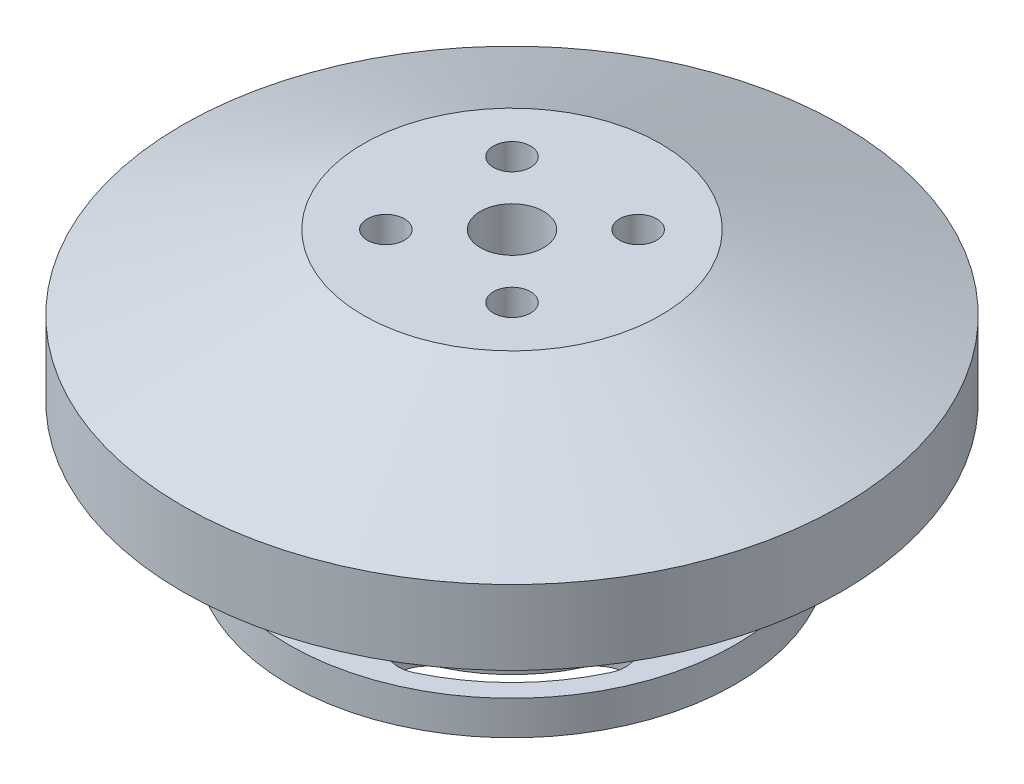
SolidWorks part; units mm, degrees
ref_plane "Plan de face" through (0, 0, 0) normal (0, 0, 1) x (1, 0, 0)
ref_plane "Plan de dessus" through (0, 0, 0) normal (0, 1, 0) x (1, 0, 0)
ref_plane "Plan de droite" through (0, 0, 0) normal (1, 0, 0) x (0, 0, -1)
sketch "Esquisse1" plane through (0, 0, 0) normal (0, 1, 0) x (1, 0, 0)
  circle A0 centre (0, 0) radius 22.175
  dimension "D1" = 44.35
extrude "Boss.-Extru.1" add sketch "Esquisse1" along normal blind 5
sketch "Esquisse2" plane through (0, 0, 0) normal (0, 0, 1) x (1, 0, 0)
  line L0 (0, 17.6967) -> (0, -9.3383) construction
  line L1 (0, 10) -> (-10, 10)
  line L2 (-10, 10) -> (-22.175, 5)
  line L3 (-22.175, 5) -> (0, 5)
  line L4 (22.175, 5) -> (-22.175, 5) construction
  line L5 (0, 5) -> (0, 10)
  dimension "D1" = 20
  dimension "D2" = 5
revolve "Révolution1" add sketch "Esquisse2" angle 360 about L0
chamfer "Chanfrein1" [suppressed] distance 0.5 angle 45
sketch "Esquisse5" [suppressed] plane through (0, 0, 0) normal (0, 0, 1) x (1, 0, 0)
  line L0 (0, 15.7888) -> (0, -12.4636) construction
  line L6 (0, 9) -> (0, 1)
  line L11 (9.8027, 9) -> (-10, 9)
  line L12 (-22.175, 1) -> (21.175, 1)
  line L13 (20.7612, 4.4996) -> (9.8027, 9)
  line L14 (21.175, 4.0858) -> (20.7612, 4.4996)
  line L15 (21.175, 1) -> (21.175, 4.0858)
  line L16 (9.8027, 9) -> (0, 9)
  line L17 (0, 1) -> (21.175, 1)
  line L18 (20.7612, 4.4996) -> (9.8027, 9)
  line L19 (21.175, 4.0858) -> (20.7612, 4.4996)
  line L20 (21.175, 1) -> (21.175, 4.0858)
  dimension "D1" = 1
revolve "Enlèvement de matière-Révolution1" [suppressed] cut sketch "Esquisse5" angle 360 about L6
sketch "Esquisse6" plane through (0, 10, 0) normal (0, 1, 0) x (1, 0, 0)
  line L0 (0, 6) -> (0, 0) construction
  line L1 (0, 0) -> (4.2426, 4.2426) construction
  circle A0 centre (0, 0) radius 6 construction
  point P3 (4.2426, 4.2426)
  point P9 (4.2426, -4.2426)
  point P10 (-4.2426, -4.2426)
  point P11 (-4.2426, 4.2426)
  point P12 (0, 0)
  dimension "D1" = 12
  dimension "D2" = 45
  dimension "D3" = 4
hole_wizard "Trou taraudé M31" positions "Esquisse3D1" profile "Esquisse7" tap size "M3" standard "ISO"
sketch3d "Esquisse3D1"
  point P0 (4.2426, 10, -4.2426)
  point P3 (4.2426, 10, 4.2426)
  point P6 (-4.2426, 10, 4.2426)
  point P9 (-4.2426, 10, -4.2426)
sketch "Esquisse7" plane through (4.2426, 10, -4.2426) normal (1, 0, 0) x (0, 0, 1)
  line L0 (0, 0) -> (0, 6.2511)
  line L1 (0, 6.2511) -> (1.25, 5.5)
  line L2 (1.25, 5.5) -> (1.25, 0)
  line L5 (1.25, 0) -> (0, 0)
  line L10 (0, 6.2511) -> (-1.25, 5.5) construction
  line L11 (0, -6.35) -> (0, 107.95) construction
  dimension "Diamètre du trou pour taraudage" = 2.5
  dimension "Profondeur du trou pour taraudage" = 5.5
  dimension "Angle de pointe" = 118
cosmetic thread "Filetage de perçage1" parameters "D1"=1, "D2"=3
cosmetic thread "Filetage de perçage2" parameters "D1"=1, "D2"=3
cosmetic thread "Filetage de perçage3" parameters "D1"=1, "D2"=3
cosmetic thread "Filetage de perçage4" parameters "D1"=1, "D2"=3
sketch "Esquisse8" [suppressed] plane through (0, 10, 0) normal (0, 1, 0) x (1, 0, 0)
  line L0 (0, 24.7209) -> (0, 0) construction
  line L1 (0, 0) -> (14.6239, 23.3628) construction
  line L2 (0, 0) -> (2.8128, 22.7623) construction
  line L3 (0, 0) -> (19.245, 12.4767) construction
  circle A3 centre (0, 0) radius 22.175 construction
  arc A4 (18.1694, 12.7124) -> (3.4948, 21.8979) centre (0, 0) ccw
  arc A5 (20.0939, -9.3789) -> (20.7115, 7.9224) centre (0, 0) ccw
  arc A6 (1.9246, -22.0913) -> (17.2167, -13.9755) centre (0, 0) ccw
  arc A7 (-18.1694, -12.7124) -> (-3.4948, -21.8979) centre (0, 0) ccw
  arc A8 (-20.0939, 9.3789) -> (-20.7115, -7.9224) centre (0, 0) ccw
  arc A9 (-1.9246, 22.0913) -> (-17.2167, 13.9755) centre (0, 0) ccw
  ellipse E0 centre (14.6239, 23.3628) end of major axis (4.5893, 7.3318) minor radius 9.3493 (3.4948, 21.8979) -> (18.1694, 12.7124) ccw
  ellipse E1 centre (28.7047, -1.0246) end of major axis (8.888, -0.3173) minor radius 9.5331 (20.7115, 7.9224) -> (20.0939, -9.3789) ccw
  ellipse E2 centre (13.465, -25.3713) end of major axis (4.1692, -7.8558) minor radius 9.5331 (17.2167, -13.9755) -> (1.9246, -22.0913) ccw
  ellipse E3 centre (-15.2397, -24.3467) end of major axis (-4.7187, -7.5386) minor radius 9.5331 (-3.4948, -21.8979) -> (-18.1694, -12.7124) ccw
  ellipse E4 centre (-28.7047, 1.0246) end of major axis (-8.888, 0.3173) minor radius 9.5331 (-20.7115, -7.9224) -> (-20.0939, 9.3789) ccw
  ellipse E5 centre (-13.465, 25.3713) end of major axis (-4.1692, 7.8558) minor radius 9.5331 (-17.2167, 13.9755) -> (-1.9246, 22.0913) ccw
  point P51 (0, 0)
  dimension "D1" = 32.044
  dimension "D2" = 25
  dimension "D3" = 6
extrude "Enlèv. mat.-Extru.1" [suppressed] cut sketch "Esquisse8" against normal blind 5.5
chamfer "Chanfrein2" [suppressed] distance 0.5 angle 45
chamfer "Chanfrein3" [suppressed] distance 0.5 angle 45
chamfer "Chanfrein4" [suppressed] distance 0.25 angle 45
sketch "Esquisse9" plane through (0, 0, 0) normal (0, -1, 0) x (1, 0, 0)
  circle A0 centre (0, 0) radius 8
  dimension "D1" = 16
extrude "Boss.-Extru.2" add sketch "Esquisse9" along normal blind 6.7 and the other way blind 5.5 separate body
sketch "Esquisse10" plane through (0, -6.7, 0) normal (0, -1, 0) x (1, 0, 0)
  circle A0 centre (0, 0) radius 15
  dimension "D1" = 30
extrude "Boss.-Extru.3" add sketch "Esquisse10" along normal blind 2.3
sketch "Esquisse11" plane through (0, -9, 0) normal (0, -1, 0) x (1, 0, 0)
  point P0 (0, 12.5)
  point P5 (12.5, 0)
  point P6 (0, -12.5)
  point P7 (-12.5, 0)
  point P8 (0, 0)
  dimension "D1" = 12.5
  dimension "D2" = 4
hole_wizard "Trou taraudé M32" positions "Esquisse3D2" profile "Esquisse12" tap size "M3" standard "ISO"
sketch3d "Esquisse3D2"
  point P0 (0, -9, 12.5)
  point P3 (12.5, -9, 0)
  point P6 (-12.5, -9, 0)
  point P9 (0, -9, -12.5)
sketch "Esquisse12" plane through (0, -9, 12.5) normal (1, 0, 0) x (0, 0, -1)
  line L0 (0, 0) -> (0, 6.2511)
  line L1 (0, 6.2511) -> (1.25, 5.5)
  line L2 (1.25, 5.5) -> (1.25, 0)
  line L5 (1.25, 0) -> (0, 0)
  line L10 (0, 6.2511) -> (-1.25, 5.5) construction
  line L11 (0, -6.35) -> (0, 107.95) construction
  dimension "Diamètre du trou pour taraudage" = 2.5
  dimension "Profondeur du trou pour taraudage" = 5.5
  dimension "Angle de pointe" = 118
cosmetic thread "Filetage de perçage5" parameters "D1"=2.3, "D2"=3
cosmetic thread "Filetage de perçage6" parameters "D1"=2.3, "D2"=3
cosmetic thread "Filetage de perçage7" parameters "D1"=2.3, "D2"=3
cosmetic thread "Filetage de perçage8" parameters "D1"=2.3, "D2"=3
sketch "Esquisse13" plane through (0, -9, 0) normal (0, -1, 0) x (1, 0, 0)
  line L0 (-8.3085, 8.3085) -> (0, 0) construction
  line L1 (0, 0) -> (0, 12.5) construction
  line L2 (-4.9658, 10.6491) -> (0, 0) construction
  line L3 (0, 0) -> (-10.6491, 4.9658) construction
  circle A0 centre (0, 0) radius 11.75 construction
  arc A1 (-10.6491, 4.9658) -> (-4.9658, 10.6491) centre (0, 0) cw construction
  arc A2 (-5.7899, 12.4164) -> (-12.4164, 5.7899) centre (0, 0) ccw
  arc A3 (-4.1417, 8.8818) -> (-8.8818, 4.1417) centre (0, 0) ccw
  arc A4 (-4.1417, 8.8818) -> (-5.7899, 12.4164) centre (-4.9658, 10.6491) ccw
  arc A5 (-12.4164, 5.7899) -> (-8.8818, 4.1417) centre (-10.6491, 4.9658) ccw
  arc A6 (4.9658, 10.6491) -> (10.6491, 4.9658) centre (0, 0) cw construction
  arc A7 (12.4164, 5.7899) -> (5.7899, 12.4164) centre (0, 0) ccw
  arc A8 (8.8818, 4.1417) -> (4.1417, 8.8818) centre (0, 0) ccw
  arc A9 (8.8818, 4.1417) -> (12.4164, 5.7899) centre (10.6491, 4.9658) ccw
  arc A10 (5.7899, 12.4164) -> (4.1417, 8.8818) centre (4.9658, 10.6491) ccw
  arc A11 (10.6491, -4.9658) -> (4.9658, -10.6491) centre (0, 0) cw construction
  arc A12 (5.7899, -12.4164) -> (12.4164, -5.7899) centre (0, 0) ccw
  arc A13 (4.1417, -8.8818) -> (8.8818, -4.1417) centre (0, 0) ccw
  arc A14 (4.1417, -8.8818) -> (5.7899, -12.4164) centre (4.9658, -10.6491) ccw
  arc A15 (12.4164, -5.7899) -> (8.8818, -4.1417) centre (10.6491, -4.9658) ccw
  arc A16 (-4.9658, -10.6491) -> (-10.6491, -4.9658) centre (0, 0) cw construction
  arc A17 (-12.4164, -5.7899) -> (-5.7899, -12.4164) centre (0, 0) ccw
  arc A18 (-8.8818, -4.1417) -> (-4.1417, -8.8818) centre (0, 0) ccw
  arc A19 (-8.8818, -4.1417) -> (-12.4164, -5.7899) centre (-10.6491, -4.9658) ccw
  arc A20 (-5.7899, -12.4164) -> (-4.1417, -8.8818) centre (-4.9658, -10.6491) ccw
  point P6 (-8.3085, 8.3085)
  point P21 (8.3085, 8.3085)
  point P28 (8.3085, -8.3085)
  point P35 (-8.3085, -8.3085)
  point P40 (0, 0)
  dimension "D1" = 23.5
  dimension "D4" = 1.95
  dimension "D2" = 45
  dimension "D3" = 40
  dimension "D5" = 4
extrude "Enlèv. mat.-Extru.2" cut sketch "Esquisse13" against normal blind 2.3
chamfer "Chanfrein5" [suppressed] distance 0.25 angle 45
sketch "Esquisse14" plane through (0, 10, 0) normal (0, 1, 0) x (1, 0, 0)
  circle A0 centre (0, 0) radius 2.125
  dimension "D1" = 4.25
extrude "Enlèv. mat.-Extru.3" cut sketch "Esquisse14" against normal through all
sketch "Esquisse15" plane through (0, 0, 0) normal (0, -1, 0) x (1, 0, 0)
  circle A0 centre (0, 0) radius 21
  dimension "D1" = 42
extrude "Enlèv. mat.-Extru.4" cut sketch "Esquisse15" against normal blind 2.3
sketch "Esquisse16" plane through (0, 5.5, 0) normal (0, 1, 0) x (1, 0, 0)
  circle A0 centre (0, 0) radius 7.5
  dimension "D1" = 15
extrude "Enlèv. mat.-Extru.5" cut sketch "Esquisse16" against normal blind 6.3 flip side to cut
chamfer "Chanfrein6" [suppressed] distance 0.25 angle 45
chamfer "Chanfrein7" [suppressed] distance 0.2 angle 45
sketch "Esquisse17" plane through (0, 10, 0) normal (0, 1, 0) x (1, 0, 0)
  circle A0 centre (0, 0) radius 2
  dimension "D1" = 4
chamfer "Chanfrein9" [suppressed] distance 0.2 angle 45
sketch "Esquisse18" [suppressed] plane through (0, 1, 0) normal (0, 1, 0) x (1, 0, 0)
  circle A1 centre (0, 0) radius 21.175
  circle A2 centre (0, 0) radius 21.175
  dimension "D1" = 0
extrude "Enlèv. mat.-Extru.6" [suppressed] cut sketch "Esquisse18" against normal blind 0.75
sketch "Esquisse19" [suppressed] plane through (0, 0.25, 0) normal (0, 1, 0) x (1, 0, 0)
  line L0 (-25.0719, 0) -> (0, 0) construction
  line L1 (0, 0) -> (-27.069, -9.8523) construction
  line L2 (-19.8075, -4.2102) -> (-19.0739, -4.0543)
  line L3 (-17.8797, -9.5068) -> (-17.2175, -9.1547)
  line L4 (-18.6419, -5.7209) -> (-7.8006, -1.775)
  line L5 (-17.9579, -7.6003) -> (-7.1166, -3.6544)
  line L6 (-19.0739, -4.0543) -> (0, 0) construction
  line L7 (-19.4743, 1) -> (-7.9373, 1)
  line L8 (-19.4743, -1) -> (-7.9373, -1)
  line L9 (-20.0529, -2.8183) -> (-19.3102, -2.7139)
  line L10 (-20.0529, 2.8183) -> (-19.3102, 2.7139)
  line L11 (-17.9579, 7.6003) -> (-7.1166, 3.6544)
  line L12 (-18.6419, 5.7209) -> (-7.8006, 1.775)
  line L13 (-19.8075, 4.2102) -> (-19.0739, 4.0543)
  line L14 (-17.8797, 9.5068) -> (-17.2175, 9.1547)
  line L15 (-14.2754, 13.2839) -> (-5.4375, 5.868)
  line L16 (-15.561, 11.7518) -> (-6.7231, 4.3359)
  line L17 (-17.173, 10.7309) -> (-16.5369, 10.3334)
  line L18 (-13.5499, 15.0487) -> (-13.048, 14.4913)
  line L19 (-8.8711, 17.3653) -> (-3.1026, 7.3739)
  line L20 (-10.6032, 16.3653) -> (-4.8347, 6.3739)
  line L21 (-12.4671, 15.9572) -> (-12.0054, 15.3662)
  line L22 (-7.5858, 18.7755) -> (-7.3048, 18.0801)
  line L23 (-2.3969, 19.3521) -> (-0.3935, 7.9903)
  line L24 (-4.3665, 19.0048) -> (-2.3631, 7.643)
  line L25 (-6.2576, 19.2589) -> (-6.0258, 18.5456)
  line L26 (-0.7067, 20.2377) -> (-0.6805, 19.4881)
  line L27 (4.3665, 19.0048) -> (2.3631, 7.643)
  line L28 (2.3969, 19.3521) -> (0.3935, 7.9903)
  line L29 (0.7067, 20.2377) -> (0.6805, 19.4881)
  line L30 (6.2576, 19.2589) -> (6.0258, 18.5456)
  line L31 (10.6032, 16.3653) -> (4.8347, 6.3739)
  line L32 (8.8711, 17.3653) -> (3.1026, 7.3739)
  line L33 (7.5858, 18.7755) -> (7.3048, 18.0801)
  line L34 (12.4671, 15.9572) -> (12.0054, 15.3662)
  line L35 (15.561, 11.7518) -> (6.7231, 4.3359)
  line L36 (14.2754, 13.2839) -> (5.4375, 5.868)
  line L37 (13.5499, 15.0487) -> (13.048, 14.4913)
  line L38 (17.173, 10.7309) -> (16.5369, 10.3334)
  line L39 (18.6419, 5.7209) -> (7.8006, 1.775)
  line L40 (17.9579, 7.6003) -> (7.1166, 3.6544)
  line L41 (17.8797, 9.5068) -> (17.2175, 9.1547)
  line L42 (19.8075, 4.2102) -> (19.0739, 4.0543)
  line L43 (19.4743, -1) -> (7.9373, -1)
  line L44 (19.4743, 1) -> (7.9373, 1)
  line L45 (20.0529, 2.8183) -> (19.3102, 2.7139)
  line L46 (20.0529, -2.8183) -> (19.3102, -2.7139)
  line L47 (17.9579, -7.6003) -> (7.1166, -3.6544)
  line L48 (18.6419, -5.7209) -> (7.8006, -1.775)
  line L49 (19.8075, -4.2102) -> (19.0739, -4.0543)
  line L50 (17.8797, -9.5068) -> (17.2175, -9.1547)
  line L51 (14.2754, -13.2839) -> (5.4375, -5.868)
  line L52 (15.561, -11.7518) -> (6.7231, -4.3359)
  line L53 (17.173, -10.7309) -> (16.5369, -10.3334)
  line L54 (13.5499, -15.0487) -> (13.048, -14.4913)
  line L55 (8.8711, -17.3653) -> (3.1026, -7.3739)
  line L56 (10.6032, -16.3653) -> (4.8347, -6.3739)
  line L57 (12.4671, -15.9572) -> (12.0054, -15.3662)
  line L58 (7.5858, -18.7755) -> (7.3048, -18.0801)
  line L59 (2.3969, -19.3521) -> (0.3935, -7.9903)
  line L60 (4.3665, -19.0048) -> (2.3631, -7.643)
  line L61 (6.2576, -19.2589) -> (6.0258, -18.5456)
  line L62 (0.7067, -20.2377) -> (0.6805, -19.4881)
  line L63 (-4.3665, -19.0048) -> (-2.3631, -7.643)
  line L64 (-2.3969, -19.3521) -> (-0.3935, -7.9903)
  line L65 (-0.7067, -20.2377) -> (-0.6805, -19.4881)
  line L66 (-6.2576, -19.2589) -> (-6.0258, -18.5456)
  line L67 (-10.6032, -16.3653) -> (-4.8347, -6.3739)
  line L68 (-8.8711, -17.3653) -> (-3.1026, -7.3739)
  line L69 (-7.5858, -18.7755) -> (-7.3048, -18.0801)
  line L70 (-12.4671, -15.9572) -> (-12.0054, -15.3662)
  line L71 (-15.561, -11.7518) -> (-6.7231, -4.3359)
  line L72 (-14.2754, -13.2839) -> (-5.4375, -5.868)
  line L73 (-13.5499, -15.0487) -> (-13.048, -14.4913)
  line L74 (-17.173, -10.7309) -> (-16.5369, -10.3334)
  arc A0 (-19.8075, -4.2102) -> (-17.8797, -9.5068) centre (0, 0) ccw
  arc A1 (-19.0739, -4.0543) -> (-18.6419, -5.7209) centre (0, 0) ccw
  circle A2 centre (0, 0) radius 8 construction
  arc A3 (-17.9579, -7.6003) -> (-17.2175, -9.1547) centre (0, 0) ccw
  arc A4 (-19.4743, -1) -> (-19.3102, -2.7139) centre (0, 0) ccw
  arc A5 (-20.0529, 2.8183) -> (-20.0529, -2.8183) centre (0, 0) ccw
  arc A6 (-19.3102, 2.7139) -> (-19.4743, 1) centre (0, 0) ccw
  arc A7 (-18.6419, 5.7209) -> (-19.0739, 4.0543) centre (0, 0) ccw
  arc A8 (-17.8797, 9.5068) -> (-19.8075, 4.2102) centre (0, 0) ccw
  arc A9 (-17.2175, 9.1547) -> (-17.9579, 7.6003) centre (0, 0) ccw
  arc A10 (-15.561, 11.7518) -> (-16.5369, 10.3334) centre (0, 0) ccw
  arc A11 (-13.5499, 15.0487) -> (-17.173, 10.7309) centre (0, 0) ccw
  arc A12 (-13.048, 14.4913) -> (-14.2754, 13.2839) centre (0, 0) ccw
  arc A13 (-10.6032, 16.3653) -> (-12.0054, 15.3662) centre (0, 0) ccw
  arc A14 (-7.5858, 18.7755) -> (-12.4671, 15.9572) centre (0, 0) ccw
  arc A15 (-7.3048, 18.0801) -> (-8.8711, 17.3653) centre (0, 0) ccw
  arc A16 (-4.3665, 19.0048) -> (-6.0258, 18.5456) centre (0, 0) ccw
  arc A17 (-0.7067, 20.2377) -> (-6.2576, 19.2589) centre (0, 0) ccw
  arc A18 (-0.6805, 19.4881) -> (-2.3969, 19.3521) centre (0, 0) ccw
  arc A19 (2.3969, 19.3521) -> (0.6805, 19.4881) centre (0, 0) ccw
  arc A20 (6.2576, 19.2589) -> (0.7067, 20.2377) centre (0, 0) ccw
  arc A21 (6.0258, 18.5456) -> (4.3665, 19.0048) centre (0, 0) ccw
  arc A22 (8.8711, 17.3653) -> (7.3048, 18.0801) centre (0, 0) ccw
  arc A23 (12.4671, 15.9572) -> (7.5858, 18.7755) centre (0, 0) ccw
  arc A24 (12.0054, 15.3662) -> (10.6032, 16.3653) centre (0, 0) ccw
  arc A25 (14.2754, 13.2839) -> (13.048, 14.4913) centre (0, 0) ccw
  arc A26 (17.173, 10.7309) -> (13.5499, 15.0487) centre (0, 0) ccw
  arc A27 (16.5369, 10.3334) -> (15.561, 11.7518) centre (0, 0) ccw
  arc A28 (17.9579, 7.6003) -> (17.2175, 9.1547) centre (0, 0) ccw
  arc A29 (19.8075, 4.2102) -> (17.8797, 9.5068) centre (0, 0) ccw
  arc A30 (19.0739, 4.0543) -> (18.6419, 5.7209) centre (0, 0) ccw
  arc A31 (19.4743, 1) -> (19.3102, 2.7139) centre (0, 0) ccw
  arc A32 (20.0529, -2.8183) -> (20.0529, 2.8183) centre (0, 0) ccw
  arc A33 (19.3102, -2.7139) -> (19.4743, -1) centre (0, 0) ccw
  arc A34 (18.6419, -5.7209) -> (19.0739, -4.0543) centre (0, 0) ccw
  arc A35 (17.8797, -9.5068) -> (19.8075, -4.2102) centre (0, 0) ccw
  arc A36 (17.2175, -9.1547) -> (17.9579, -7.6003) centre (0, 0) ccw
  arc A37 (15.561, -11.7518) -> (16.5369, -10.3334) centre (0, 0) ccw
  arc A38 (13.5499, -15.0487) -> (17.173, -10.7309) centre (0, 0) ccw
  arc A39 (13.048, -14.4913) -> (14.2754, -13.2839) centre (0, 0) ccw
  arc A40 (10.6032, -16.3653) -> (12.0054, -15.3662) centre (0, 0) ccw
  arc A41 (7.5858, -18.7755) -> (12.4671, -15.9572) centre (0, 0) ccw
  arc A42 (7.3048, -18.0801) -> (8.8711, -17.3653) centre (0, 0) ccw
  arc A43 (4.3665, -19.0048) -> (6.0258, -18.5456) centre (0, 0) ccw
  arc A44 (0.7067, -20.2377) -> (6.2576, -19.2589) centre (0, 0) ccw
  arc A45 (0.6805, -19.4881) -> (2.3969, -19.3521) centre (0, 0) ccw
  arc A46 (-2.3969, -19.3521) -> (-0.6805, -19.4881) centre (0, 0) ccw
  arc A47 (-6.2576, -19.2589) -> (-0.7067, -20.2377) centre (0, 0) ccw
  arc A48 (-6.0258, -18.5456) -> (-4.3665, -19.0048) centre (0, 0) ccw
  arc A49 (-8.8711, -17.3653) -> (-7.3048, -18.0801) centre (0, 0) ccw
  arc A50 (-12.4671, -15.9572) -> (-7.5858, -18.7755) centre (0, 0) ccw
  arc A51 (-12.0054, -15.3662) -> (-10.6032, -16.3653) centre (0, 0) ccw
  arc A52 (-14.2754, -13.2839) -> (-13.048, -14.4913) centre (0, 0) ccw
  arc A53 (-17.173, -10.7309) -> (-13.5499, -15.0487) centre (0, 0) ccw
  arc A54 (-16.5369, -10.3334) -> (-15.561, -11.7518) centre (0, 0) ccw
  arc A55 (-7.1166, -3.6544) -> (-6.7231, -4.3359) centre (0, 0) ccw
  arc A56 (-7.9373, -1) -> (-7.8006, -1.775) centre (0, 0) ccw
  arc A57 (-7.8006, 1.775) -> (-7.9373, 1) centre (0, 0) ccw
  arc A58 (-6.7231, 4.3359) -> (-7.1166, 3.6544) centre (0, 0) ccw
  arc A59 (-4.8347, 6.3739) -> (-5.4375, 5.868) centre (0, 0) ccw
  arc A60 (-2.3631, 7.643) -> (-3.1026, 7.3739) centre (0, 0) ccw
  arc A61 (0.3935, 7.9903) -> (-0.3935, 7.9903) centre (0, 0) ccw
  arc A62 (3.1026, 7.3739) -> (2.3631, 7.643) centre (0, 0) ccw
  arc A63 (5.4375, 5.868) -> (4.8347, 6.3739) centre (0, 0) ccw
  arc A64 (7.1166, 3.6544) -> (6.7231, 4.3359) centre (0, 0) ccw
  arc A65 (7.9373, 1) -> (7.8006, 1.775) centre (0, 0) ccw
  arc A66 (7.8006, -1.775) -> (7.9373, -1) centre (0, 0) ccw
  arc A67 (6.7231, -4.3359) -> (7.1166, -3.6544) centre (0, 0) ccw
  arc A68 (4.8347, -6.3739) -> (5.4375, -5.868) centre (0, 0) ccw
  arc A69 (2.3631, -7.643) -> (3.1026, -7.3739) centre (0, 0) ccw
  arc A70 (-0.3935, -7.9903) -> (0.3935, -7.9903) centre (0, 0) ccw
  arc A71 (-3.1026, -7.3739) -> (-2.3631, -7.643) centre (0, 0) ccw
  arc A72 (-5.4375, -5.868) -> (-4.8347, -6.3739) centre (0, 0) ccw
  point P153 (0, 0)
  point P187 (0, 0)
  dimension "D2" = 20.25
  dimension "D4" = 16
  dimension "D1" = 20
  dimension "D3" = 0.75
  dimension "D5" = 2
  dimension "D6" = 1
  dimension "D7" = 8
  dimension "D8" = 18
  dimension "D9" = 18
extrude "Boss.-Extru.5" [suppressed] add sketch "Esquisse19" along normal blind 3.75 separate body
ref_plane "Plan2" [suppressed] through (-9.7372, 0, 16.8653) normal (-0.5, 0, 0.866) x (0.866, 0, 0.5)
ref_plane "Plan3" [suppressed] through (-9.4872, 0, 16.4323) normal (-0.5, 0, 0.866) x (0.866, 0, 0.5)
sketch "Esquisse21" [suppressed] plane through (-9.4872, 0, 16.4323) normal (-0.5, 0, 0.866) x (0.866, 0, 0.5)
  line L0 (2.8183, 4) -> (-2.8183, 4) construction
  line L1 (-1, 4.5) -> (1, 4.5)
  line L2 (-1.5, 4) -> (-1.5, 0.25)
  line L3 (-1, -0.25) -> (1, -0.25)
  line L4 (1.5, 4) -> (1.5, 0.25)
  line L5 (-1, 4) -> (-1, 0.25) construction
  line L6 (-2.8183, 0.25) -> (2.8183, 0.25) construction
  line L7 (1, 4) -> (1, 0.25) construction
  arc A0 (-1.5, 0.25) -> (-1, -0.25) centre (-1, 0.25) ccw
  arc A1 (1, -0.25) -> (1.5, 0.25) centre (1, 0.25) ccw
  arc A2 (1, 4.5) -> (1.5, 4) centre (1, 4) cw
  arc A3 (-1, 4.5) -> (-1.5, 4) centre (-1, 4) ccw
  dimension "D5" = 0.5
  dimension "D1" = 0.5
  dimension "D2" = 0.5
  dimension "D3" = 0.5
  dimension "D4" = 0.5
ref_plane "Plan4" [suppressed] through (-8.1881, 4, 17.1823) normal (0, -1, 0) x (-1, 0, 0)
sketch "Esquisse22" [suppressed] plane through (-8.1881, 4, 17.1823) normal (0, -1, 0) x (-1, 0, 0)
  circle A0 centre (0, 0) radius 0.375
  dimension "D1" = 0.75
sweep "Balayage3" [suppressed] add profiles "Esquisse22" path "Esquisse21"
pattern_linear "Répétition linéaire3" [suppressed] count 15 spacing 0.7
pattern_circular "Répétition circulaire3" [suppressed] count 18 every 20
